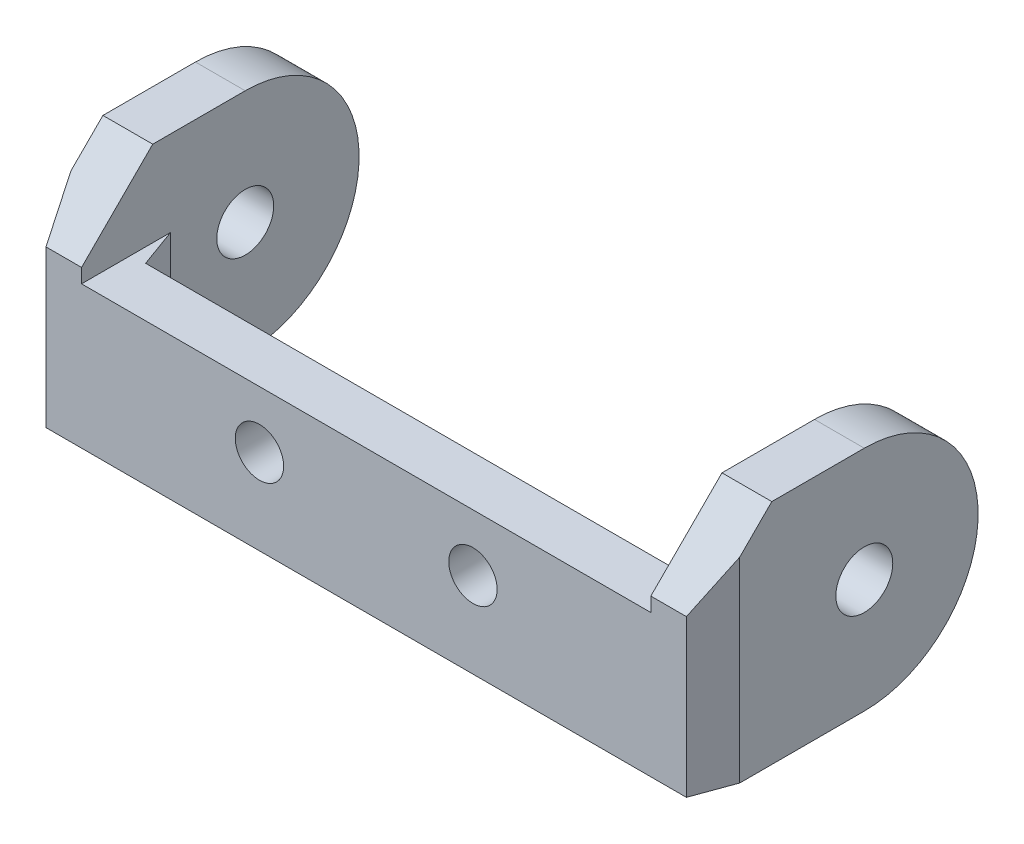
SolidWorks part; units mm, degrees
ref_plane "前视基准面" through (0, 0, 0) normal (0, 0, 1) x (1, 0, 0)
ref_plane "上视基准面" through (0, 0, 0) normal (0, 1, 0) x (1, 0, 0)
ref_plane "右视基准面" through (0, 0, 0) normal (1, 0, 0) x (0, 0, -1)
sketch "草图1" plane through (0, 0, 0) normal (0, 0, 1) x (1, 0, 0)
  line L1 (27.5, -15) -> (-19.5, -15)
  line L2 (27.5, -15) -> (27.5, 1)
  line L3 (27.5, 1) -> (-19.5, 1)
  line L4 (-19.5, -15) -> (-19.5, 1)
  point P0 (0, 0)
  dimension "D1" = 16
  dimension "D2" = 47
extrude "凸台-拉伸1" add sketch "草图1" along normal blind 3.5
ref_plane "基准面1" through (27.5, 0, 0) normal (1, 0, 0) x (0, 0, -1)
sketch "草图2" plane through (27.5, 0, 0) normal (1, 0, 0) x (0, 0, -1)
  line L0 (0, 1) -> (0, -15)
  line L1 (0, -15) -> (0, 1) construction
  line L2 (0, -15) -> (8, -15)
  line L4 (8, 1) -> (0, 1)
  line L5 (0, -7) -> (30, -7) construction
  line L6 (15.9696, -7.6972) -> (8, -7) construction
  line L7 (8, -7) -> (12.5886, -0.4468) construction
  circle A2 centre (8, -7) radius 2
  circle A3 centre (8, -7) radius 8 construction
  arc A21 (8, 1) -> (8, -15) centre (8, -7) cw
  point P25 (7.6327, 8)
  dimension "D2" = 16
  dimension "D3" = 4
  dimension "D4" = 60
  dimension "D5" = 5
  dimension "D7" = 8
extrude "凸台-拉伸2" add sketch "草图2" against normal blind 3.5
ref_plane "基准面2" through (4, 0, 0) normal (-1, 0, 0) x (0, 0, 1)
mirror "镜向1" about plane through (4, 0, 0) normal (-1, 0, 0) of "凸台-拉伸2"
sketch "草图3" plane through (0, 0, 3.5) normal (0, 0, 1) x (1, 0, 0)
  line L0 (-19.5, -15) -> (27.5, -15) construction
  line L1 (-26.9, 0) -> (34.9, 0) construction
  line L2 (27.5, 1) -> (-19.5, 1) construction
  line L4 (4, 0) -> (4, 1) construction
  circle A2 centre (11.5, -9) radius 1.7
  circle A4 centre (-3.5, -9) radius 1.7
  dimension "D1" = 15
  dimension "D3" = 3.4
  dimension "D5" = 6
extrude "切除-拉伸1" cut sketch "草图3" against normal blind 10
sketch "草图4" plane through (0, 0, 3.5) normal (0, 0, 1) x (1, 0, 0)
  line L1 (24, 1) -> (27.5, 1) construction
  line L12 (24, 1) -> (27.5, 1) construction
  line L14 (24, 1) -> (-16, 1)
  line L15 (24, 1) -> (24, -5)
  line L16 (24, -5) -> (-16, -5)
  line L17 (-16, 1) -> (-16, -5)
  point P5 (19, 1)
  dimension "D1" = 40
  dimension "D2" = 6
extrude "切除-拉伸2" cut sketch "草图4" against normal blind 10
chamfer "倒角4" distance 1 angle 70 4 edges at (-19.5, -7, 3.5) (27.5, -7, 3.5) (24, -10, 0) (-16, -10, 0)
chamfer "Chamfer1" distance 5 angle 45 1 edges at (-17.25, 1, 3.5)
